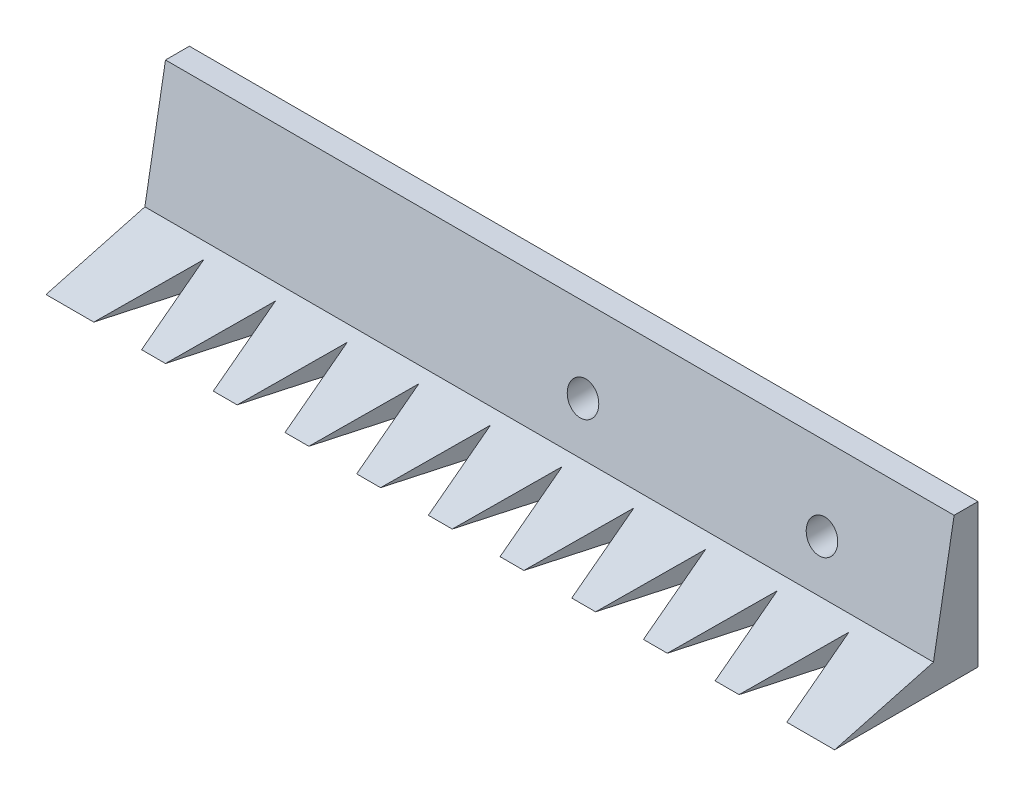
SolidWorks part; units mm, degrees
ref_plane "Front Plane" through (0, 0, 0) normal (0, 0, 1) x (1, 0, 0)
ref_plane "Top Plane" through (0, 0, 0) normal (0, 1, 0) x (1, 0, 0)
ref_plane "Right Plane" through (0, 0, 0) normal (1, 0, 0) x (0, 0, -1)
sketch "Sketch1" plane through (0, 0, 0) normal (1, 0, 0) x (0, 0, -1)
  line L0 (0, 0) -> (0, 30)
  line L3 (-30, 0) -> (0, 0)
  line L4 (-30, 0) -> (-9.3124, 5.5432)
  line L5 (-9.3124, 5.5432) -> (-5, 30)
  line L6 (-5, 30) -> (0, 30)
  dimension "D1" = 30
  dimension "D2" = 30
  dimension "D3" = 10
  dimension "D4" = 15
  dimension "D5" = 5
extrude "Boss-Extrude1" add sketch "Sketch1" along normal blind 100
sketch "Sketch2" plane through (0, 0, 0) normal (0, 0, -1) x (-1, 0, 0)
  line L0 (-100, 15) -> (0, 15) construction
  line L1 (-100, 0) -> (-100, 30) construction
  line L2 (0, 0) -> (0, 30) construction
  line L3 (-100, 30) -> (0, 30) construction
  point P8 (-75, 15)
  point P9 (-25, 15)
  dimension "D1" = 15
  dimension "D2" = 25
  dimension "D3" = 25
hole_wizard "M3 Clearance Hole1" positions "Sketch2" profile "Sketch3" hole size "M3" standard "ANSI Metric" end condition through all
sketch "Sketch3" plane through (25, 15, 0) normal (1, 0, 0) x (0, 1, 0)
  line L0 (0, 0) -> (0, 30)
  line L1 (0, 30) -> (1.7, 30)
  line L2 (1.7, 30) -> (1.7, 0)
  line L5 (1.7, 0) -> (0, 0)
  line L11 (0, -6.35) -> (0, 107.95) construction
  dimension "Thru Hole Dia." = 3.4
  dimension "Thru Hole Depth" = 30
ref_plane "Plane1" through (0, 0, 2.5) normal (0, 0, -1) x (-1, 0, 0)
sketch "Sketch4" plane through (0, 0, 2.5) normal (0, 0, -1) x (-1, 0, 0)
  circle A0 centre (-75, 15) radius 3.25
  circle A1 centre (-25, 15) radius 3.25
  dimension "D1" = 6.5
extrude "Cut-Extrude1" cut sketch "Sketch4" against normal through all
sketch "Sketch6" plane through (0, 0, 0) normal (-1, 0, 0) x (0, 0, 1)
  line L5 (0, 0) -> (30, 0)
  line L6 (30, 0) -> (9.3124, 5.5432)
  line L7 (9.3124, 5.5432) -> (5, 30)
  line L8 (5, 30) -> (0, 30)
  line L9 (0, 30) -> (0, 0)
  line L10 (0, 0) -> (30, 0)
  line L11 (30, 0) -> (9.3124, 5.5432)
  line L12 (9.3124, 5.5432) -> (5, 30)
  line L13 (5, 30) -> (0, 30)
  line L14 (0, 30) -> (0, 0)
  dimension "D1" = 0
extrude "Boss-Extrude2" add sketch "Sketch6" along normal blind 65
sketch "Sketch7" plane through (0, 0, 0) normal (0, 1, 0) x (1, 0, 0)
  line L0 (-55, -30) -> (-50, -12)
  line L1 (100, -30) -> (-65, -30) construction
  line L2 (-50, -12) -> (-45, -30)
  line L3 (-45, -30) -> (-55, -30)
  dimension "D1" = 18
  dimension "D2" = 10
  dimension "D3" = 10
extrude "Cut-Extrude2" cut sketch "Sketch7" along normal through all both and the other way through all
pattern_linear "LPattern1" count 10 spacing 15 along (1, 0, 0) of "Cut-Extrude2"
